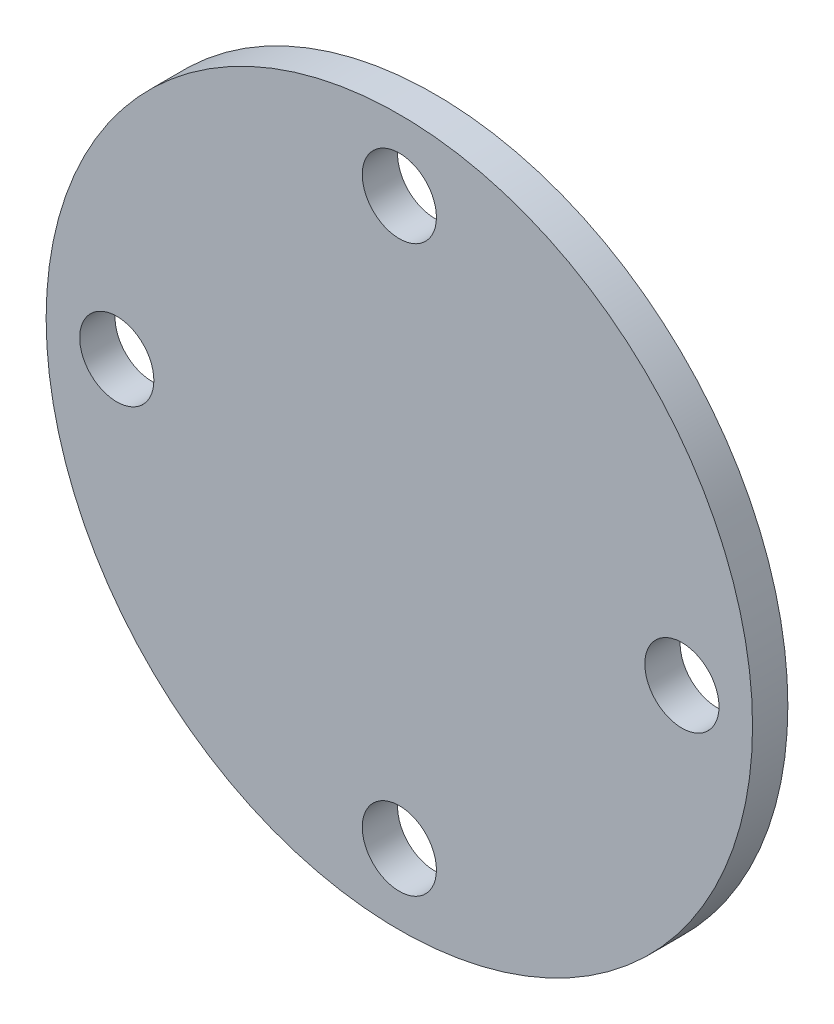
SolidWorks part; units mm, degrees
ref_plane "前视基准面" through (0, 0, 0) normal (0, 0, 1) x (1, 0, 0)
ref_plane "上视基准面" through (0, 0, 0) normal (0, 1, 0) x (1, 0, 0)
ref_plane "右视基准面" through (0, 0, 0) normal (1, 0, 0) x (0, 0, -1)
other "Configuration Table"
sketch "草图1" plane through (0, 0, 0) normal (0, 0, 1) x (1, 0, 0)
  circle A0 centre (0, 0) radius 10
  dimension "D1" = 20
extrude "凸台-拉伸1" add sketch "草图1" along normal blind 1
sketch "草图2" plane through (0, 0, 1) normal (0, 0, 1) x (1, 0, 0)
  line L0 (0, 0) -> (0, 8) construction
  circle A0 centre (0, 8) radius 1.05
  circle A1 centre (8, 0) radius 1.05
  circle A2 centre (0, -8) radius 1.05
  circle A3 centre (-8, 0) radius 1.05
  point P13 (0, 0)
  dimension "D1" = 4
extrude "切除-拉伸1" cut sketch "草图2" against normal through all
